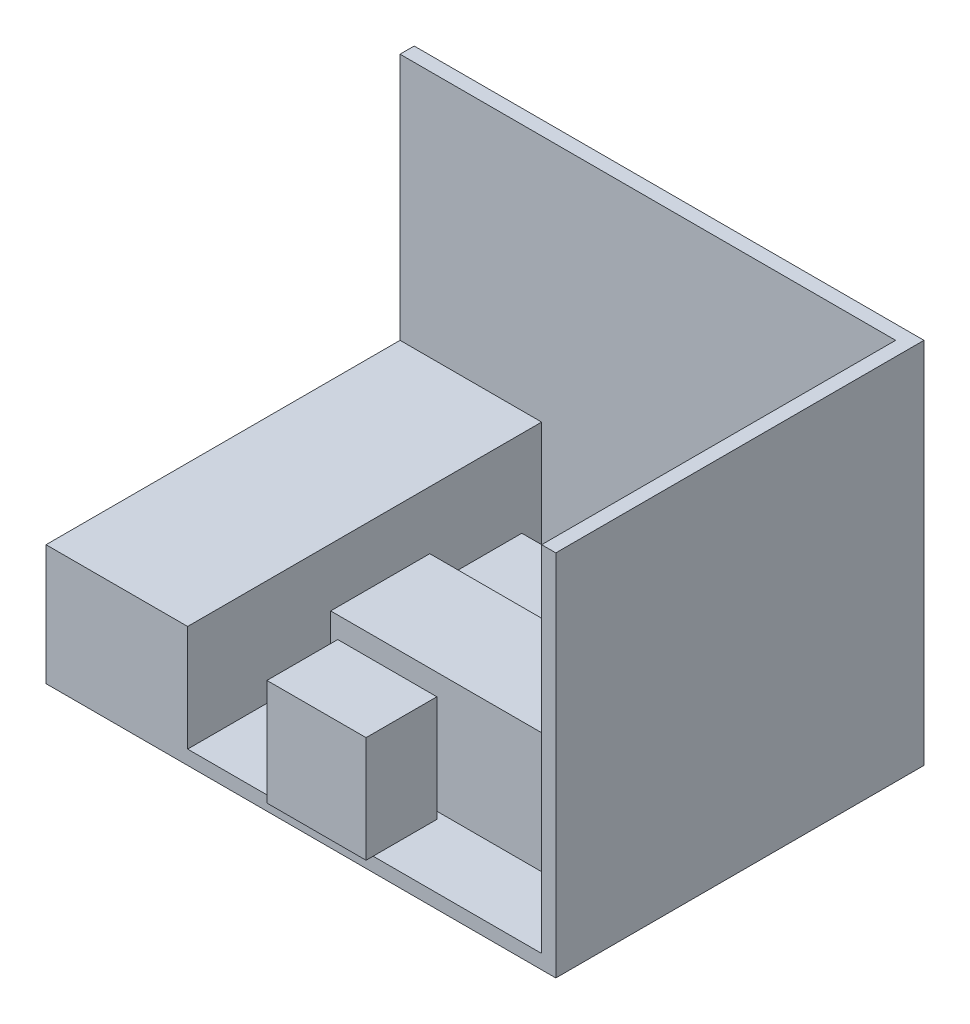
SolidWorks part; units mm, degrees
ref_plane "Front Plane" through (0, 0, 0) normal (0, 0, 1) x (1, 0, 0)
ref_plane "Top Plane" through (0, 0, 0) normal (0, 1, 0) x (1, 0, 0)
ref_plane "Right Plane" through (0, 0, 0) normal (1, 0, 0) x (0, 0, -1)
sketch "Sketch1" plane through (0, 0, 0) normal (0, 1, 0) x (1, 0, 0)
  line L1 (0, 2600) -> (3600, 2600)
  line L2 (0, 2600) -> (0, 0)
  line L3 (0, 0) -> (3600, 0)
  line L4 (3600, 2600) -> (3600, 0)
  dimension "D1" = 3600
  dimension "D2" = 2600
extrude "Boss-Extrude1" add sketch "Sketch1" along normal blind 100
sketch "Sketch2" plane through (0, 100, 0) normal (0, 1, 0) x (1, 0, 0)
  line L0 (3600, 0) -> (3500, 0)
  line L1 (0, 0) -> (3600, 0) construction
  line L2 (3500, 0) -> (3500, 2500)
  line L3 (3500, 2500) -> (0, 2500)
  line L4 (0, 2600) -> (0, 0) construction
  line L5 (0, 2500) -> (0, 2600)
  line L6 (0, 2600) -> (3600, 2600)
  line L7 (3600, 2600) -> (3600, 0)
  dimension "D1" = 100
  dimension "D2" = 100
extrude "Boss-Extrude2" add sketch "Sketch2" along normal blind 2500
sketch "Sketch4" plane through (0, 100, 0) normal (0, 1, 0) x (1, 0, 0)
  line L0 (0, 0) -> (3500, 0) construction
  line L1 (3510, 500) -> (1510, 500)
  line L2 (3510, 500) -> (3510, 1200)
  line L3 (3510, 1200) -> (1510, 1200)
  line L4 (1510, 500) -> (1510, 1200)
  line L6 (3500, 2500) -> (3500, 0) construction
  dimension "D1" = 2000
  dimension "D2" = 700
  dimension "D3" = 500
  dimension "D4" = 10
extrude "Boss-Extrude3" add sketch "Sketch4" along normal blind 850
sketch "Sketch5" plane through (0, 100, 0) normal (0, 1, 0) x (1, 0, 0)
  line L0 (0, 2500) -> (3500, 2500) construction
  line L1 (0, 0) -> (1000, 0)
  line L2 (0, 0) -> (0, 2500)
  line L3 (0, 2500) -> (1000, 2500)
  line L4 (1000, 0) -> (1000, 2500)
  dimension "D1" = 1000
extrude "Boss-Extrude4" add sketch "Sketch5" along normal blind 750
sketch "Sketch6" plane through (0, 100, 0) normal (0, 1, 0) x (1, 0, 0)
  line L0 (3500, 1200) -> (1510, 1200) construction
  line L1 (1610, 1250) -> (2310, 1250)
  line L2 (1610, 1250) -> (1610, 1750)
  line L3 (1610, 1750) -> (2310, 1750)
  line L4 (2310, 1250) -> (2310, 1750)
  line L6 (1510, 1200) -> (1510, 500) construction
  dimension "D1" = 500
  dimension "D2" = 700
  dimension "D3" = 50
  dimension "D4" = 100
extrude "Boss-Extrude5" add sketch "Sketch6" along normal blind 750
sketch "Sketch7" plane through (0, 100, 0) normal (0, 1, 0) x (1, 0, 0)
  line L0 (1610, 1250) -> (1610, 1200) construction
  line L1 (1610, 450) -> (2310, 450)
  line L2 (1610, 450) -> (1610, -50)
  line L3 (1610, -50) -> (2310, -50)
  line L4 (2310, 450) -> (2310, -50)
  line L5 (1610, 1750) -> (2310, 1750) construction
  line L6 (1610, 1750) -> (1610, 1250) construction
  line L7 (1610, 1250) -> (2310, 1250) construction
  line L8 (2310, 1750) -> (2310, 1250) construction
  line L9 (3500, 1200) -> (1510, 1200) construction
  line L10 (1610, 450) -> (1610, 500) construction
  line L11 (1510, 500) -> (3500, 500) construction
extrude "Boss-Extrude6" add sketch "Sketch7" along normal blind 750
